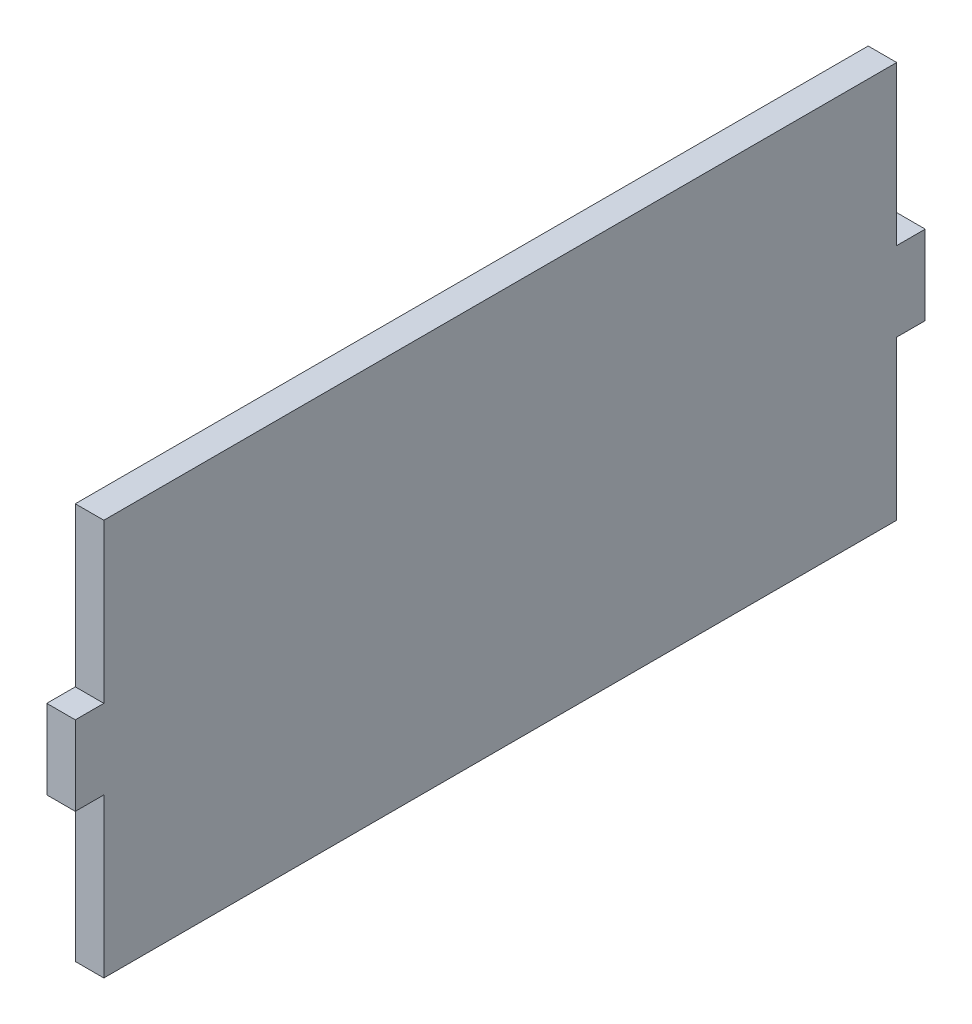
SolidWorks part; units mm, degrees
ref_plane "Front Plane" through (0, 0, 0) normal (0, 0, 1) x (1, 0, 0)
ref_plane "Top Plane" through (0, 0, 0) normal (0, 1, 0) x (1, 0, 0)
ref_plane "Right Plane" through (0, 0, 0) normal (1, 0, 0) x (0, 0, -1)
sketch "Sketch1" plane through (0, 0, 0) normal (1, 0, 0) x (0, 0, -1)
  line L1 (0, 0) -> (500, 0)
  line L2 (0, 0) -> (0, -100)
  line L3 (0, -250) -> (500, -250)
  line L4 (500, 0) -> (500, -100)
  line L6 (-18, -100) -> (0, -100)
  line L7 (-18, -100) -> (-18, -150)
  line L8 (-18, -150) -> (0, -150)
  line L10 (518, -150) -> (500, -150)
  line L11 (518, -100) -> (518, -150)
  line L12 (0, -150) -> (0, -250)
  line L13 (518, -100) -> (500, -100)
  line L14 (500, -150) -> (500, -250)
  dimension "D1" = 500
  dimension "D2" = 250
  dimension "D3" = 50
extrude "Boss-Extrude1" add sketch "Sketch1" along normal blind 18
